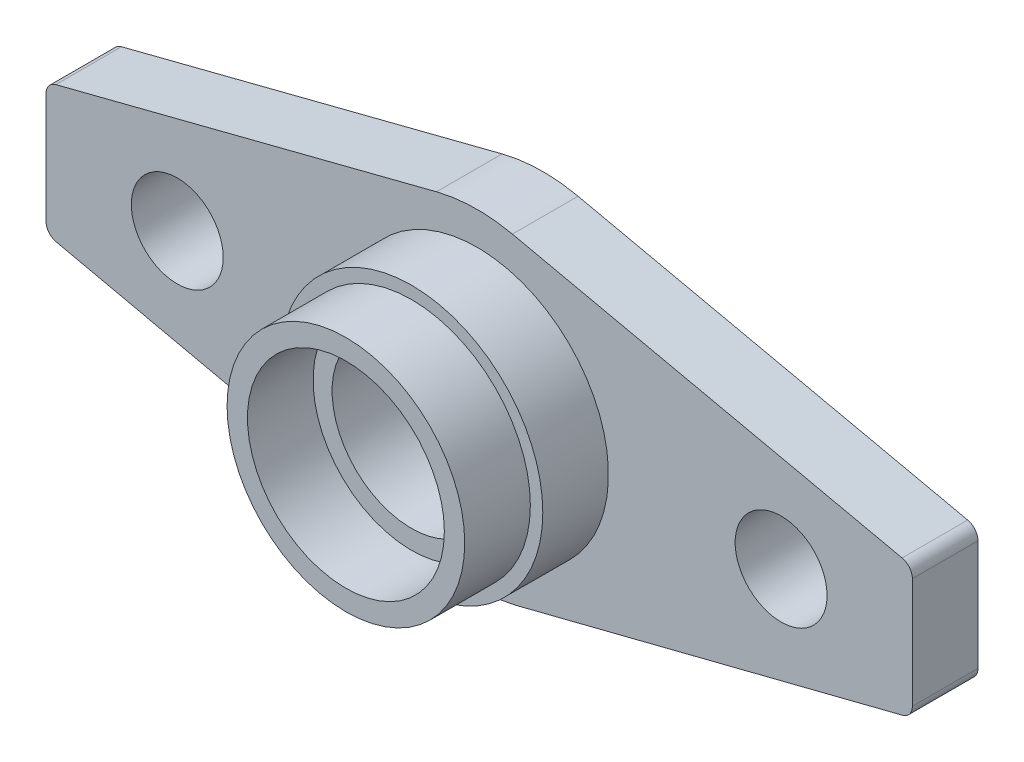
SolidWorks part; units mm, degrees
ref_plane "Front Plane" through (0, 0, 0) normal (0, 0, 1) x (1, 0, 0)
ref_plane "Top Plane" through (0, 0, 0) normal (0, 1, 0) x (1, 0, 0)
ref_plane "Right Plane" through (0, 0, 0) normal (1, 0, 0) x (0, 0, -1)
sketch "Sketch2" plane through (0, 0, 0) normal (0, 0, 1) x (1, 0, 0)
  line L0 (-32.0945, 4.6825) -> (-3.1018, 12.1091)
  line L2 (-32.8464, -4.7078) -> (-32.8464, 3.7138)
  line L4 (33.1536, -3.7073) -> (33.1536, 4.7106)
  line L5 (-32.8464, -0.497) -> (33.1536, 0.5016) construction
  line L7 (-32.0631, -5.684) -> (-2.846, -12.1717)
  line L8 (2.6821, 12.2089) -> (32.3682, 5.6873)
  line L9 (2.9386, -12.1497) -> (32.3995, -4.6766)
  circle A0 centre (0, 0) radius 7.5
  arc A2 (32.3682, 5.6873) -> (33.1536, 4.7106) centre (32.1536, 4.7106) cw
  arc A3 (32.3995, -4.6766) -> (33.1536, -3.7073) centre (32.1536, -3.7073) ccw
  arc A4 (-32.0631, -5.684) -> (-32.8464, -4.7078) centre (-31.8464, -4.7078) cw
  arc A5 (-32.0945, 4.6825) -> (-32.8464, 3.7138) centre (-31.8464, 3.7138) ccw
  arc A9 (-2.846, -12.1717) -> (2.9386, -12.1497) centre (0, 0) ccw
  arc A10 (2.6821, 12.2089) -> (-3.1018, 12.1091) centre (0, 0) ccw
  circle A11 centre (-22.8464, -0.3457) radius 3.5
  circle A12 centre (23.1536, 0.3503) radius 3.5
  point P0 (0, 0)
  point P4 (33.1536, 5.5147)
  point P19 (33.1536, -4.4853)
  point P22 (-32.8464, -5.5101)
  point P25 (-32.8464, 4.4899)
  dimension "D1" = 25
  dimension "D4" = 1
  dimension "D5" = 12.5
  dimension "D7" = 15
  dimension "D8" = 10
  dimension "D6" = 10
  dimension "D2" = 10
  dimension "D3" = 10
  dimension "D9" = 66
extrude "Boss-Extrude1" add sketch "Sketch2" along normal blind 5
sketch "Sketch3" plane through (0, 0, 5) normal (0, 0, 1) x (1, 0, 0)
  circle A0 centre (0, 0) radius 10
  circle A1 centre (0, 0) radius 6.0524
  dimension "D1" = 20
extrude "Boss-Extrude2" add sketch "Sketch3" along normal blind 5
sketch "Sketch5" plane through (0, 0, 10) normal (0, 0, 1) x (1, 0, 0)
  circle A1 centre (0, 0) radius 7.5
  circle A2 centre (0, 0) radius 9.0524
  circle A3 centre (0, 0) radius 9.0524
  dimension "D2" = 15
  dimension "D1" = 3
extrude "Boss-Extrude3" add sketch "Sketch5" along normal blind 5
